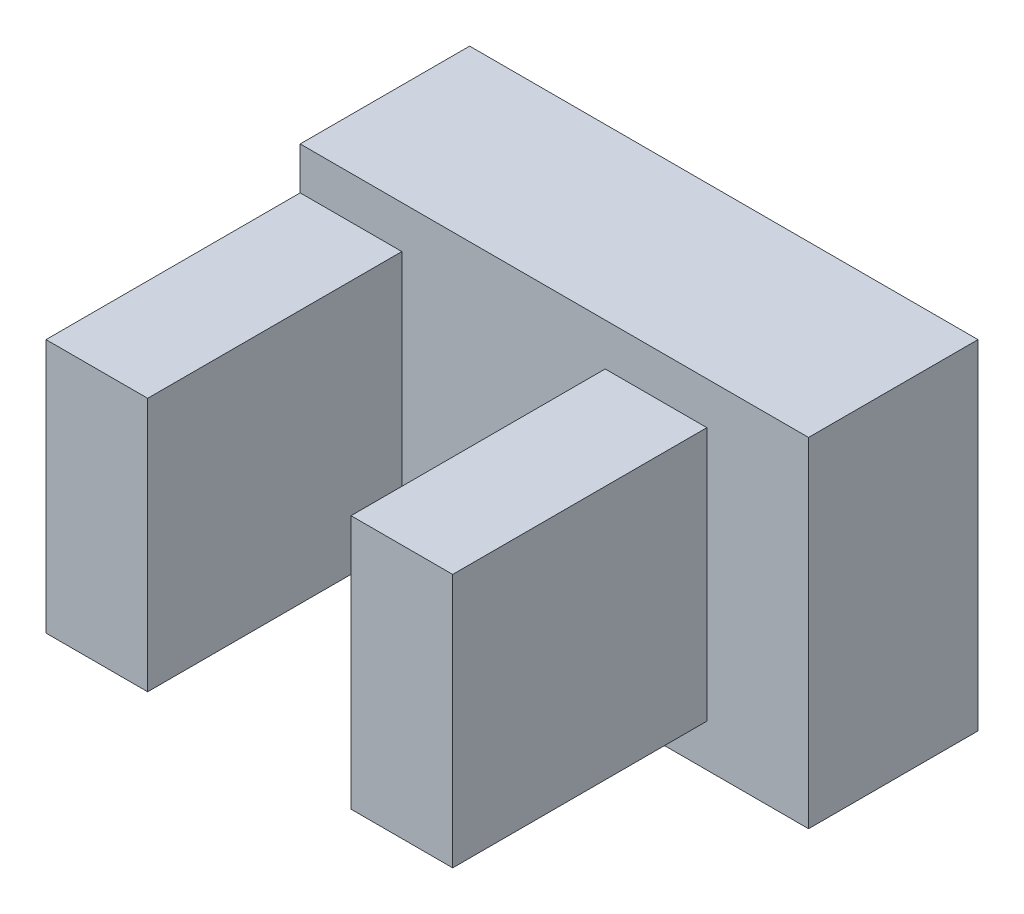
SolidWorks part; units mm, degrees
ref_plane "前视基准面" through (0, 0, 0) normal (0, 0, 1) x (1, 0, 0)
ref_plane "上视基准面" through (0, 0, 0) normal (0, 1, 0) x (1, 0, 0)
ref_plane "右视基准面" through (0, 0, 0) normal (1, 0, 0) x (0, 0, -1)
other "Configuration Table"
sketch "草图8" plane through (0, 0, 0) normal (0, 0, 1) x (1, 0, 0)
  line L1 (-30, 20) -> (30, 20)
  line L2 (-30, 20) -> (-30, -20)
  line L3 (-30, -20) -> (30, -20)
  line L4 (30, 20) -> (30, -20)
extrude "凸台-拉伸1" add sketch "草图8" along normal blind 20
sketch "草图9" plane through (0, 0, 20) normal (0, 0, 1) x (1, 0, 0)
  line L1 (-30, 15) -> (-18, 15)
  line L2 (-30, 15) -> (-30, -15)
  line L3 (-30, -15) -> (-18, -15)
  line L4 (-18, 15) -> (-18, -15)
extrude "凸台-拉伸2" add sketch "草图9" along normal blind 30
sketch "草图10" plane through (0, 0, 20) normal (0, 0, 1) x (1, 0, 0)
  line L1 (6, 15) -> (18, 15)
  line L2 (6, 15) -> (6, -15)
  line L3 (6, -15) -> (18, -15)
  line L4 (18, 15) -> (18, -15)
extrude "凸台-拉伸3" add sketch "草图10" along normal blind 30
